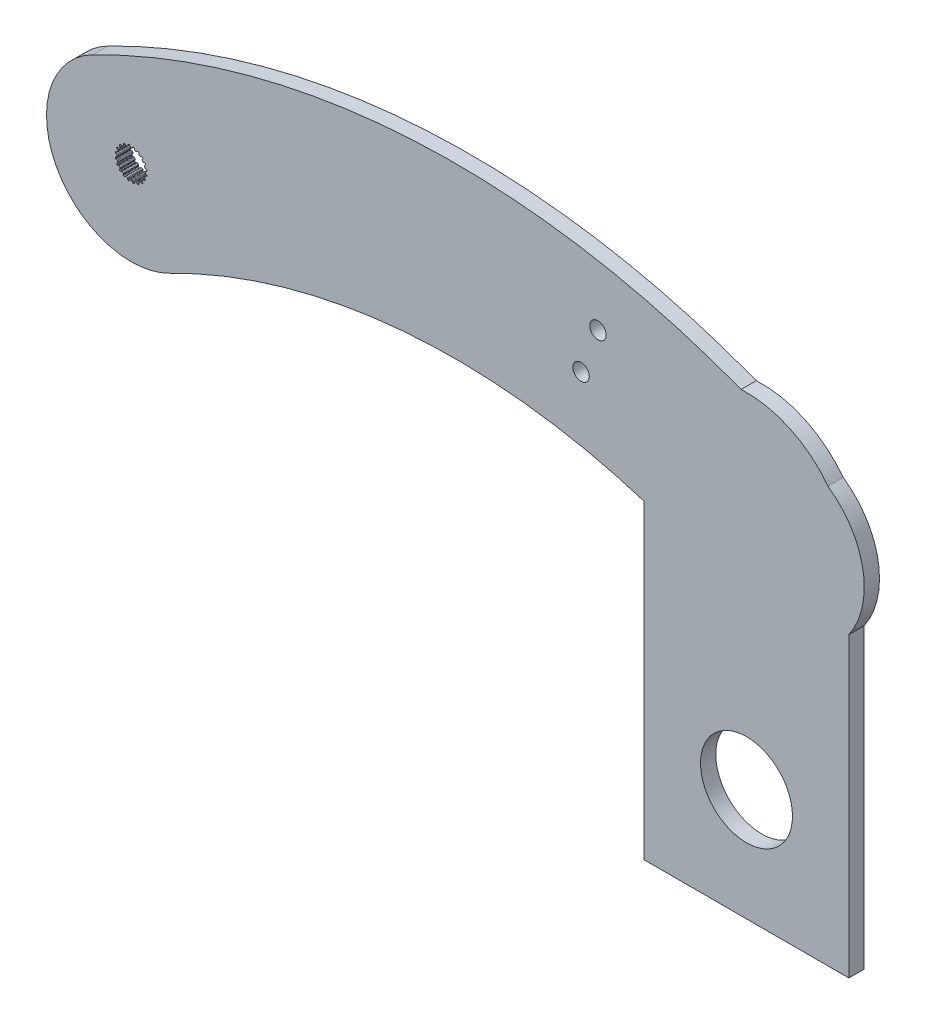
SolidWorks part; units mm, degrees
ref_plane "Front Plane" through (0, 0, 0) normal (0, 0, 1) x (1, 0, 0)
ref_plane "Top Plane" through (0, 0, 0) normal (0, 1, 0) x (1, 0, 0)
ref_plane "Right Plane" through (0, 0, 0) normal (1, 0, 0) x (0, 0, -1)
sketch "Sketch1" plane through (0, 0, 0) normal (0, 0, 1) x (1, 0, 0)
  line L0 (-0.1069, 2.9699) -> (0.1069, 2.9699)
  line L1 (0.3159, 3.2375) -> (0.2537, 3.0575)
  line L2 (-0.2964, 3.2367) -> (-0.2318, 3.0575)
  line L3 (-0.2964, 3.2367) -> (0.3159, 3.2375) construction
  line L4 (0, 3.3252) -> (0, 0) construction
  line L5 (-0.2318, 3.0575) -> (0.2537, 3.0575) construction
  line L6 (-0.4281, 3.3241) -> (0.4281, 3.3263) construction
  line L7 (0.7183, 3.1698) -> (0.7244, 2.9795)
  line L8 (0.816, 2.8576) -> (1.0195, 2.7915)
  line L9 (1.3009, 2.9815) -> (1.1862, 2.8295)
  line L10 (1.6627, 2.7927) -> (1.6097, 2.6099)
  line L11 (1.6591, 2.4655) -> (1.8322, 2.3398)
  line L12 (2.1585, 2.4335) -> (2.0025, 2.3245)
  line L13 (2.4443, 2.1423) -> (2.3374, 1.9847)
  line L14 (2.3398, 1.8322) -> (2.4655, 1.6591)
  line L15 (2.8049, 1.6474) -> (2.6228, 1.5919)
  line L16 (2.9866, 1.2821) -> (2.8363, 1.1653)
  line L17 (2.7915, 1.0195) -> (2.8576, 0.816)
  line L18 (3.1767, 0.7) -> (2.9863, 0.7035)
  line L19 (3.2367, 0.2964) -> (3.0575, 0.2318)
  line L20 (2.9699, 0.1069) -> (2.9699, -0.1069)
  line L21 (3.2375, -0.3159) -> (3.0575, -0.2537)
  line L22 (3.1698, -0.7183) -> (2.9795, -0.7244)
  line L23 (2.8576, -0.816) -> (2.7915, -1.0195)
  line L24 (2.9815, -1.3009) -> (2.8295, -1.1862)
  line L25 (2.7927, -1.6627) -> (2.6099, -1.6097)
  line L26 (2.4655, -1.6591) -> (2.3398, -1.8322)
  line L27 (2.4335, -2.1585) -> (2.3245, -2.0025)
  line L28 (2.1423, -2.4443) -> (1.9847, -2.3374)
  line L29 (1.8322, -2.3398) -> (1.6591, -2.4655)
  line L30 (1.6474, -2.8049) -> (1.5919, -2.6228)
  line L31 (1.2821, -2.9866) -> (1.1653, -2.8363)
  line L32 (1.0195, -2.7915) -> (0.816, -2.8576)
  line L33 (0.7, -3.1767) -> (0.7035, -2.9863)
  line L34 (0.2964, -3.2367) -> (0.2318, -3.0575)
  line L35 (0.1069, -2.9699) -> (-0.1069, -2.9699)
  line L36 (-0.3159, -3.2375) -> (-0.2537, -3.0575)
  line L37 (-0.7183, -3.1698) -> (-0.7244, -2.9795)
  line L38 (-0.816, -2.8576) -> (-1.0195, -2.7915)
  line L39 (-1.3009, -2.9815) -> (-1.1862, -2.8295)
  line L40 (-1.6627, -2.7927) -> (-1.6097, -2.6099)
  line L41 (-1.6591, -2.4655) -> (-1.8322, -2.3398)
  line L42 (-2.1585, -2.4335) -> (-2.0025, -2.3245)
  line L43 (-2.4443, -2.1423) -> (-2.3374, -1.9847)
  line L44 (-2.3398, -1.8322) -> (-2.4655, -1.6591)
  line L45 (-2.8049, -1.6474) -> (-2.6228, -1.5919)
  line L46 (-2.9866, -1.2821) -> (-2.8363, -1.1653)
  line L47 (-2.7915, -1.0195) -> (-2.8576, -0.816)
  line L48 (-3.1767, -0.7) -> (-2.9863, -0.7035)
  line L49 (-3.2367, -0.2964) -> (-3.0575, -0.2318)
  line L50 (-2.9699, -0.1069) -> (-2.9699, 0.1069)
  line L51 (-3.2375, 0.3159) -> (-3.0575, 0.2537)
  line L52 (-3.1698, 0.7183) -> (-2.9795, 0.7244)
  line L53 (-2.8576, 0.816) -> (-2.7915, 1.0195)
  line L54 (-2.9815, 1.3009) -> (-2.8295, 1.1862)
  line L55 (-2.7927, 1.6627) -> (-2.6099, 1.6097)
  line L56 (-2.4655, 1.6591) -> (-2.3398, 1.8322)
  line L57 (-2.4335, 2.1585) -> (-2.3245, 2.0025)
  line L58 (-2.1423, 2.4443) -> (-1.9847, 2.3374)
  line L59 (-1.8322, 2.3398) -> (-1.6591, 2.4655)
  line L60 (-1.6474, 2.8049) -> (-1.5919, 2.6228)
  line L61 (-1.2821, 2.9866) -> (-1.1653, 2.8363)
  line L62 (-1.0195, 2.7915) -> (-0.816, 2.8576)
  line L63 (-0.7, 3.1767) -> (-0.7035, 2.9863)
  line L64 (0.4281, 3.3263) -> (0.62, 3.2938)
  line L65 (1.4351, 3.0312) -> (1.6075, 2.9409)
  line L66 (2.3015, 2.4394) -> (2.4376, 2.3003)
  line L67 (2.9427, 1.6088) -> (3.0291, 1.4344)
  line L68 (3.2958, 0.6207) -> (3.3241, 0.4281)
  line L69 (3.3263, -0.4281) -> (3.2938, -0.62)
  line L70 (3.0312, -1.4351) -> (2.9409, -1.6075)
  line L71 (2.4394, -2.3015) -> (2.3003, -2.4376)
  line L72 (1.6088, -2.9427) -> (1.4344, -3.0291)
  line L73 (0.6207, -3.2958) -> (0.4281, -3.3241)
  line L74 (-0.4281, -3.3263) -> (-0.62, -3.2938)
  line L75 (-1.4351, -3.0312) -> (-1.6075, -2.9409)
  line L76 (-2.3015, -2.4394) -> (-2.4376, -2.3003)
  line L77 (-2.9427, -1.6088) -> (-3.0291, -1.4344)
  line L78 (-3.2958, -0.6207) -> (-3.3241, -0.4281)
  line L79 (-3.3263, 0.4281) -> (-3.2938, 0.62)
  line L80 (-3.0312, 1.4351) -> (-2.9409, 1.6075)
  line L81 (-2.4394, 2.3015) -> (-2.3003, 2.4376)
  line L82 (-1.6088, 2.9427) -> (-1.4344, 3.0291)
  line L83 (-0.6207, 3.2958) -> (-0.4281, 3.3241)
  line L84 (-8.0971, 15.8327) -> (8.0971, -15.8327) construction
  line L85 (144.3983, 15.8327) -> (128.2041, -15.8327) construction
  line L86 (0, 0) -> (136.3012, 0) construction
  arc A0 (0.2537, 3.0575) -> (0.1069, 2.9699) centre (0.1283, 3.1009) cw
  arc A1 (-0.2318, 3.0575) -> (-0.1069, 2.9699) centre (-0.1069, 3.1026) ccw
  arc A2 (0.62, 3.2938) -> (0.7183, 3.1698) centre (0.5856, 3.1656) cw
  arc A3 (0.7244, 2.9795) -> (0.816, 2.8576) centre (0.857, 2.9838) ccw
  arc A4 (-0.4281, 3.3241) -> (-0.2964, 3.2367) centre (-0.4213, 3.1916) cw
  arc A5 (0.4281, 3.3263) -> (0.3159, 3.2375) centre (0.4413, 3.1942) ccw
  arc A6 (1.1862, 2.8295) -> (1.0195, 2.7915) centre (1.0802, 2.9095) cw
  arc A7 (1.4351, 3.0312) -> (1.3009, 2.9815) centre (1.4068, 2.9015) ccw
  arc A8 (1.6075, 2.9409) -> (1.6627, 2.7927) centre (1.5352, 2.8297) cw
  arc A9 (1.6097, 2.6099) -> (1.6591, 2.4655) centre (1.7371, 2.5729) ccw
  arc A10 (2.0025, 2.3245) -> (1.8322, 2.3398) centre (1.9264, 2.4332) cw
  arc A11 (2.3015, 2.4394) -> (2.1585, 2.4335) centre (2.2346, 2.3248) ccw
  arc A12 (2.4376, 2.3003) -> (2.4443, 2.1423) centre (2.3345, 2.2168) cw
  arc A13 (2.3374, 1.9847) -> (2.3398, 1.8322) centre (2.4472, 1.9102) ccw
  arc A14 (2.6228, 1.5919) -> (2.4655, 1.6591) centre (2.5841, 1.7189) cw
  arc A15 (2.9427, 1.6088) -> (2.8049, 1.6474) centre (2.8436, 1.5205) ccw
  arc A16 (3.0291, 1.4344) -> (2.9866, 1.2821) centre (2.9052, 1.3869) cw
  arc A17 (2.8363, 1.1653) -> (2.7915, 1.0195) centre (2.9177, 1.0605) ccw
  arc A18 (2.9863, 0.7035) -> (2.8576, 0.816) centre (2.9887, 0.8362) cw
  arc A19 (3.2958, 0.6207) -> (3.1767, 0.7) centre (3.1743, 0.5673) ccw
  arc A20 (3.3241, 0.4281) -> (3.2367, 0.2964) centre (3.1916, 0.4213) cw
  arc A21 (3.0575, 0.2318) -> (2.9699, 0.1069) centre (3.1026, 0.1069) ccw
  arc A22 (3.0575, -0.2537) -> (2.9699, -0.1069) centre (3.1009, -0.1283) cw
  arc A23 (3.3263, -0.4281) -> (3.2375, -0.3159) centre (3.1942, -0.4413) ccw
  arc A24 (3.2938, -0.62) -> (3.1698, -0.7183) centre (3.1656, -0.5856) cw
  arc A25 (2.9795, -0.7244) -> (2.8576, -0.816) centre (2.9838, -0.857) ccw
  arc A26 (2.8295, -1.1862) -> (2.7915, -1.0195) centre (2.9095, -1.0802) cw
  arc A27 (3.0312, -1.4351) -> (2.9815, -1.3009) centre (2.9015, -1.4068) ccw
  arc A28 (2.9409, -1.6075) -> (2.7927, -1.6627) centre (2.8297, -1.5352) cw
  arc A29 (2.6099, -1.6097) -> (2.4655, -1.6591) centre (2.5729, -1.7371) ccw
  arc A30 (2.3245, -2.0025) -> (2.3398, -1.8322) centre (2.4332, -1.9264) cw
  arc A31 (2.4394, -2.3015) -> (2.4335, -2.1585) centre (2.3248, -2.2346) ccw
  arc A32 (2.3003, -2.4376) -> (2.1423, -2.4443) centre (2.2168, -2.3345) cw
  arc A33 (1.9847, -2.3374) -> (1.8322, -2.3398) centre (1.9102, -2.4472) ccw
  arc A34 (1.5919, -2.6228) -> (1.6591, -2.4655) centre (1.7189, -2.5841) cw
  arc A35 (1.6088, -2.9427) -> (1.6474, -2.8049) centre (1.5205, -2.8436) ccw
  arc A36 (1.4344, -3.0291) -> (1.2821, -2.9866) centre (1.3869, -2.9052) cw
  arc A37 (1.1653, -2.8363) -> (1.0195, -2.7915) centre (1.0605, -2.9177) ccw
  arc A38 (0.7035, -2.9863) -> (0.816, -2.8576) centre (0.8362, -2.9887) cw
  arc A39 (0.6207, -3.2958) -> (0.7, -3.1767) centre (0.5673, -3.1743) ccw
  arc A40 (0.4281, -3.3241) -> (0.2964, -3.2367) centre (0.4213, -3.1916) cw
  arc A41 (0.2318, -3.0575) -> (0.1069, -2.9699) centre (0.1069, -3.1026) ccw
  arc A42 (-0.2537, -3.0575) -> (-0.1069, -2.9699) centre (-0.1283, -3.1009) cw
  arc A43 (-0.4281, -3.3263) -> (-0.3159, -3.2375) centre (-0.4413, -3.1942) ccw
  arc A44 (-0.62, -3.2938) -> (-0.7183, -3.1698) centre (-0.5856, -3.1656) cw
  arc A45 (-0.7244, -2.9795) -> (-0.816, -2.8576) centre (-0.857, -2.9838) ccw
  arc A46 (-1.1862, -2.8295) -> (-1.0195, -2.7915) centre (-1.0802, -2.9095) cw
  arc A47 (-1.4351, -3.0312) -> (-1.3009, -2.9815) centre (-1.4068, -2.9015) ccw
  arc A48 (-1.6075, -2.9409) -> (-1.6627, -2.7927) centre (-1.5352, -2.8297) cw
  arc A49 (-1.6097, -2.6099) -> (-1.6591, -2.4655) centre (-1.7371, -2.5729) ccw
  arc A50 (-2.0025, -2.3245) -> (-1.8322, -2.3398) centre (-1.9264, -2.4332) cw
  arc A51 (-2.3015, -2.4394) -> (-2.1585, -2.4335) centre (-2.2346, -2.3248) ccw
  arc A52 (-2.4376, -2.3003) -> (-2.4443, -2.1423) centre (-2.3345, -2.2168) cw
  arc A53 (-2.3374, -1.9847) -> (-2.3398, -1.8322) centre (-2.4472, -1.9102) ccw
  arc A54 (-2.6228, -1.5919) -> (-2.4655, -1.6591) centre (-2.5841, -1.7189) cw
  arc A55 (-2.9427, -1.6088) -> (-2.8049, -1.6474) centre (-2.8436, -1.5205) ccw
  arc A56 (-3.0291, -1.4344) -> (-2.9866, -1.2821) centre (-2.9052, -1.3869) cw
  arc A57 (-2.8363, -1.1653) -> (-2.7915, -1.0195) centre (-2.9177, -1.0605) ccw
  arc A58 (-2.9863, -0.7035) -> (-2.8576, -0.816) centre (-2.9887, -0.8362) cw
  arc A59 (-3.2958, -0.6207) -> (-3.1767, -0.7) centre (-3.1743, -0.5673) ccw
  arc A60 (-3.3241, -0.4281) -> (-3.2367, -0.2964) centre (-3.1916, -0.4213) cw
  arc A61 (-3.0575, -0.2318) -> (-2.9699, -0.1069) centre (-3.1026, -0.1069) ccw
  arc A62 (-3.0575, 0.2537) -> (-2.9699, 0.1069) centre (-3.1009, 0.1283) cw
  arc A63 (-3.3263, 0.4281) -> (-3.2375, 0.3159) centre (-3.1942, 0.4413) ccw
  arc A64 (-3.2938, 0.62) -> (-3.1698, 0.7183) centre (-3.1656, 0.5856) cw
  arc A65 (-2.9795, 0.7244) -> (-2.8576, 0.816) centre (-2.9838, 0.857) ccw
  arc A66 (-2.8295, 1.1862) -> (-2.7915, 1.0195) centre (-2.9095, 1.0802) cw
  arc A67 (-3.0312, 1.4351) -> (-2.9815, 1.3009) centre (-2.9015, 1.4068) ccw
  arc A68 (-2.9409, 1.6075) -> (-2.7927, 1.6627) centre (-2.8297, 1.5352) cw
  arc A69 (-2.6099, 1.6097) -> (-2.4655, 1.6591) centre (-2.5729, 1.7371) ccw
  arc A70 (-2.3245, 2.0025) -> (-2.3398, 1.8322) centre (-2.4332, 1.9264) cw
  arc A71 (-2.4394, 2.3015) -> (-2.4335, 2.1585) centre (-2.3248, 2.2346) ccw
  arc A72 (-2.3003, 2.4376) -> (-2.1423, 2.4443) centre (-2.2168, 2.3345) cw
  arc A73 (-1.9847, 2.3374) -> (-1.8322, 2.3398) centre (-1.9102, 2.4472) ccw
  arc A74 (-1.5919, 2.6228) -> (-1.6591, 2.4655) centre (-1.7189, 2.5841) cw
  arc A75 (-1.6088, 2.9427) -> (-1.6474, 2.8049) centre (-1.5205, 2.8436) ccw
  arc A76 (-1.4344, 3.0291) -> (-1.2821, 2.9866) centre (-1.3869, 2.9052) cw
  arc A77 (-1.1653, 2.8363) -> (-1.0195, 2.7915) centre (-1.0605, 2.9177) ccw
  arc A78 (-0.7035, 2.9863) -> (-0.816, 2.8576) centre (-0.8362, 2.9887) cw
  arc A79 (-0.6207, 3.2958) -> (-0.7, 3.1767) centre (-0.5673, 3.1743) ccw
  circle A80 centre (0, 0) radius 12.7 construction
  arc A81 (-8.0971, 15.8327) -> (144.3983, 15.8327) centre (68.1506, -133.2589) cw
  arc A82 (8.0971, -15.8327) -> (128.2041, -15.8327) centre (68.1506, -133.2589) cw
  arc A84 (-8.0971, 15.8327) -> (8.0971, -15.8327) centre (0, 0) ccw
  arc A85 (144.3983, 15.8327) -> (128.2041, -15.8327) centre (136.3012, 0) cw
  point P14 (0, 2.9699)
  point P26 (0, 0)
  point P247 (0, 0)
  dimension "D4" = 0.1327
  dimension "D8" = 20
  dimension "D9" = 25.4
  dimension "D10" = 131.8914
  dimension "D1" = 2.9699
  dimension "D2" = 0.2139
  dimension "D3" = 0.1904
  dimension "D5" = 0.0877
  dimension "D6" = 0.4855
  dimension "D7" = 0.8563
  dimension "D11" = 35.5662
  dimension "D12" = 136.3012
extrude "Boss-Extrude1" add sketch "Sketch1" along normal blind 3.2004
sketch "Sketch2" plane through (0, 0, 3.2004) normal (0, 0, 1) x (1, 0, 0)
  line L0 (129.3364, 1.5876) -> (129.6879, 2.5127) construction
  line L5 (129.6879, 2.5127) -> (136.3012, 0) construction
  line L7 (144.3983, 15.8327) -> (128.2041, -15.8327) construction
  line L19 (94.5649, 9.4501) -> (98.1166, 18.7981) construction
  line L20 (141.7724, -8.4861) -> (145.3241, 0.8619) construction
  line L24 (96.3408, 14.1241) -> (143.5482, -3.8121) construction
  circle A7 centre (98.1166, 18.7981) radius 1.7272
  circle A9 centre (141.7724, -8.4861) radius 1.7272
  circle A10 centre (145.3241, 0.8619) radius 1.7272
  circle A11 centre (94.5649, 9.4501) radius 1.7272
  circle A13 centre (129.3364, 1.5876) radius 3.429
  point P0 (129.3364, 1.5876)
  dimension "D2" = 15.203
  dimension "D3" = 6.858
  dimension "D5" = 3.4544
  dimension "D6" = 7.0746
  dimension "D8" = 96.282
  dimension "D1" = 50.5
  dimension "D4" = 10
  dimension "D7" = 0.9896
extrude "Cut-Extrude1" cut sketch "Sketch2" against normal up to surface (3.2004 mm away) up to face at (68.1506, 4.1592, 0)
sketch "Sketch3" plane through (0, 0, 3.2004) normal (0, 0, 1) x (1, 0, 0)
  line L0 (129.3364, 1.5876) -> (129.3364, -72.7318) construction
  line L1 (150.8461, 1.5876) -> (107.8268, 1.5876) construction
  line L2 (150.8461, 1.5876) -> (150.8461, -72.7318)
  line L3 (150.8461, -72.7318) -> (107.8268, -72.7318)
  line L4 (107.8268, 1.5876) -> (107.8268, -72.7318)
  arc A0 (107.8268, 1.5876) -> (150.8461, 1.5876) centre (129.3364, 1.5876) cw
  circle A1 centre (129.3364, 1.5876) radius 3.429 construction
extrude "Boss-Extrude2" add sketch "Sketch3" against normal up to surface (3.2004 mm away) up to face at (96.3894, 18.7981, 0)
sketch "Sketch4" plane through (0, 0, 3.2004) normal (0, 0, 1) x (1, 0, 0)
  line L0 (129.3364, 1.5876) -> (129.3364, -72.7318) construction
  line L1 (150.8461, 1.5876) -> (107.8268, 1.5876) construction
  circle A0 centre (129.3364, -49.2124) radius 9.6614
  dimension "D1" = 50.8
extrude "Cut-Extrude2" cut sketch "Sketch4" against normal up to surface (3.2004 mm away) up to face at (97.5988, -13.2617, 0)
